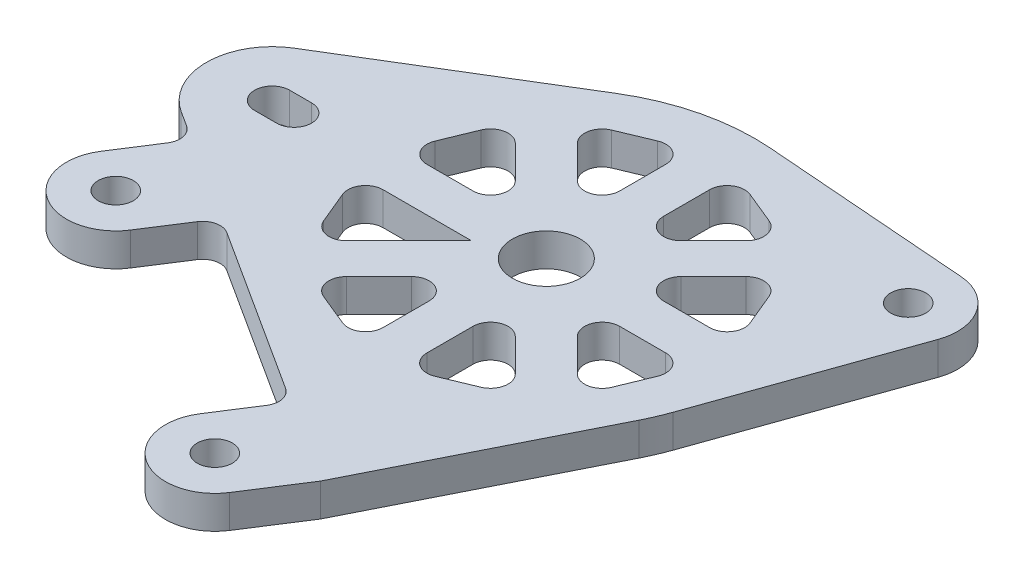
SolidWorks part; units mm, degrees
material "Thornel Mat VMA"
ref_plane "前视基准面" through (0, 0, 0) normal (0, 0, 1) x (1, 0, 0)
ref_plane "上视基准面" through (0, 0, 0) normal (0, 1, 0) x (1, 0, 0)
ref_plane "右视基准面" through (0, 0, 0) normal (1, 0, 0) x (0, 0, -1)
sketch "草图1" plane through (0, 0, 0) normal (0, 1, 0) x (1, 0, 0)
  line L0 (1.4616, 18.9437) -> (20.3462, 17.4867)
  line L1 (16.9789, -8.5274) -> (7.2713, -27.8561)
  line L2 (17.9057, -6.3549) -> (24.2408, 11.4949)
  line L3 (0, 0) -> (0, -19) construction
  line L4 (0, 0) -> (-13.435, -13.435) construction
  line L5 (-2, -4.8284) -> (-9.3986, -12.2271)
  line L6 (-9.3986, -12.2271) -> (-2, -15.2701)
  line L7 (-2, -15.2701) -> (-2, -4.8284)
  line L8 (-2, -4.8284) -> (0, 0) construction
  line L9 (-12.2118, -9.3834) -> (-4.8284, -2)
  line L10 (-4.8284, -2) -> (-15.2917, -2)
  line L11 (-15.2917, -2) -> (-12.2118, -9.3834)
  line L12 (-15.2701, 2) -> (-4.8284, 2)
  line L13 (-4.8284, 2) -> (-12.2271, 9.3986)
  line L14 (-12.2271, 9.3986) -> (-15.2701, 2)
  line L15 (0, 0) -> (-25, 0) construction
  line L17 (-9.3834, 12.2118) -> (-2, 4.8284)
  line L18 (-2, 4.8284) -> (-2, 15.2917)
  line L19 (-25, 1.6) -> (-23, 1.6)
  line L20 (-25, -1.6) -> (-23, -1.6)
  line L21 (-2, 15.2917) -> (-9.3834, 12.2118)
  line L22 (2, 15.2701) -> (2, 4.8284)
  line L23 (2, 4.8284) -> (9.3986, 12.2271)
  line L24 (9.3986, 12.2271) -> (2, 15.2701)
  line L25 (12.2118, 9.3834) -> (4.8284, 2)
  line L26 (4.8284, 2) -> (15.2917, 2)
  line L27 (15.2917, 2) -> (12.2118, 9.3834)
  line L28 (15.2701, -2) -> (4.8284, -2)
  line L29 (4.8284, -2) -> (12.2271, -9.3986)
  line L30 (12.2271, -9.3986) -> (15.2701, -2)
  line L31 (9.3834, -12.2118) -> (2, -4.8284)
  line L32 (2, -4.8284) -> (2, -15.2917)
  line L33 (2, -15.2917) -> (9.3834, -12.2118)
  line L46 (-9.88, 16.2292) -> (-28.12, 5.125)
  line L47 (-28.2423, -5.0485) -> (7.2713, -27.8561)
  line L75 (-25, 0) -> (-25, -14.2616) construction
  line L76 (-21.2136, -16.6933) -> (-17.9713, -11.6447)
  line L77 (-25.5441, -6.7813) -> (-28.7864, -11.8299)
  line L78 (-0.3015, -22.9927) -> (-3.5437, -28.0412)
  line L79 (7.2713, -27.8561) -> (4.0291, -32.9046)
  circle A15 centre (0, 0) radius 3.1
  arc A16 (-25, 1.6) -> (-25, -1.6) centre (-25, 0) ccw
  circle A21 centre (0, 0) radius 19
  arc A22 (-23, -1.6) -> (-23, 1.6) centre (-23, 0) ccw
  circle A23 centre (-25, 0) radius 6
  circle A45 centre (20, 13) radius 1.6
  circle A48 centre (0.2427, -30.4729) radius 1.6
  circle A49 centre (-25, -14.2616) radius 1.6
  circle A50 centre (-25, -14.2616) radius 4.5
  circle A51 centre (0.2427, -30.4729) radius 4.5
  circle A57 centre (0, 0) radius 10.2
  circle A58 centre (20, 13) radius 4.5
  point P10 (0, 0)
  point P11 (0, 0)
  point P34 (0, 0)
  point P37 (0, 0)
  point P46 (0, 0)
  dimension "D9" = 6.2
  dimension "D10" = 45
  dimension "D12" = 3.2
  dimension "D16" = 8
  dimension "D17" = 8
  dimension "D19" = 12
  dimension "D35" = 3.2
  dimension "D36" = 3.2
  dimension "D42" = 9
  dimension "D40" = 6
  dimension "D39" = 3.2
  dimension "D43" = 9
  dimension "D48" = 20.4
  dimension "D6" = 9
  dimension "D7" = 38
  dimension "D2" = 13
  dimension "D11" = 25
  dimension "D14" = 42.2066
  dimension "D15" = 2
  dimension "D18" = 2
  dimension "D38" = 6
  dimension "D41" = 90
  dimension "D47" = 30
  dimension "D5" = 20
  dimension "D13" = 2
extrude "凸台-拉伸1" add sketch "草图1" along normal blind 3
fillet "圆角1" radius 1.6 26 edges at (-25.5441, 1.5, 6.7813) (-17.9713, 1.5, 11.6447) (-0.3015, 1.5, 22.9927) (-15.2917, 1.5, 2) (-15.2701, 1.5, -2) (-12.2271, 1.5, -9.3986) (-4.8284, 1.5, -2) (-12.2118, 1.5, 9.3834) (-2, 1.5, 15.2701) (-2, 1.5, 4.8284) (-9.3986, 1.5, 12.2271) (2, 1.5, 15.2917) (2, 1.5, 4.8284) (4.8284, 1.5, 2) (15.2701, 1.5, 2) (12.2271, 1.5, 9.3986) (9.3834, 1.5, 12.2118) (15.2917, 1.5, -2) (12.2118, 1.5, -9.3834) (4.8284, 1.5, -2) (9.3986, 1.5, -12.2271) (2, 1.5, -4.8284) (2, 1.5, -15.2701) (-2, 1.5, -4.8284) (-9.3834, 1.5, -12.2118) (-2, 1.5, -15.2917)
equation "\"3。2\"=10"
